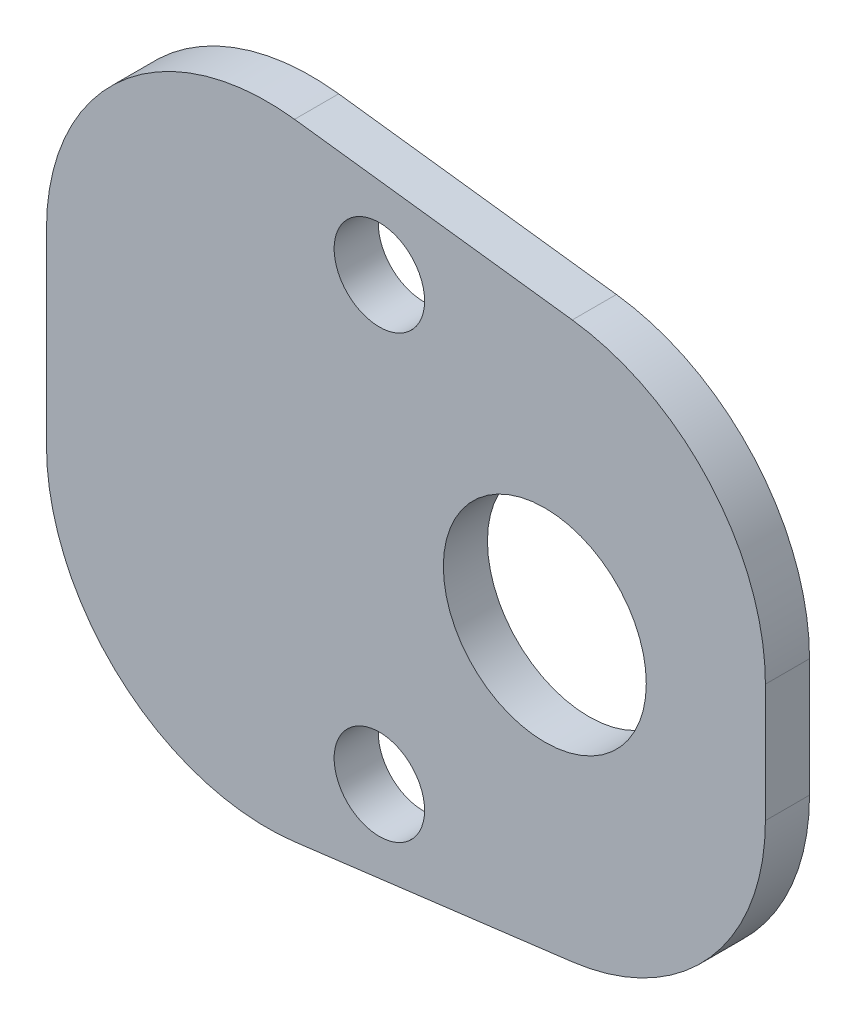
SolidWorks part; units mm, degrees
ref_plane "前视基准面" through (0, 0, 0) normal (0, 0, 1) x (1, 0, 0)
ref_plane "上视基准面" through (0, 0, 0) normal (0, 1, 0) x (1, 0, 0)
ref_plane "右视基准面" through (0, 0, 0) normal (1, 0, 0) x (0, 0, -1)
sketch "草图1" plane through (0, 0, 0) normal (0, 0, 1) x (1, 0, 0)
  line L0 (-22.499, 0) -> (-38.999, 0) construction
  line L12 (-3.7531, 12.6002) -> (-16.3433, 14.1812)
  line L36 (-9.489, 1) -> (-9.489, -1) construction
  line L40 (-0.509, 1) -> (-0.509, -1) construction
  line L41 (-3.7531, -12.6002) -> (-16.3433, -14.1812)
  line L45 (5.001, 2.6782) -> (5.001, -2.6782)
  line L47 (-27.5892, -4.2591) -> (-27.5892, 4.2591)
  circle A3 centre (-38.999, 0) radius 3 construction
  circle A6 centre (-12.499, 10) radius 2.05
  circle A37 centre (-4.999, 0) radius 4.6
  circle A43 centre (-12.499, -10) radius 2.05
  arc A47 (-3.7531, -12.6002) -> (5.001, -2.6782) centre (-4.999, -2.6782) ccw
  arc A48 (-3.7531, 12.6002) -> (5.001, 2.6782) centre (-4.999, 2.6782) cw
  arc A49 (-16.3433, 14.1812) -> (-27.5892, 4.2591) centre (-17.5892, 4.2591) ccw
  arc A50 (-27.5892, -4.2591) -> (-16.3433, -14.1812) centre (-17.5892, -4.2591) ccw
  point P7 (5.001, -11.501)
  point P11 (5.001, 11.501)
  point P14 (-27.5892, 15.5933)
  point P22 (-27.5892, -15.5933)
  dimension "D3" = 10
  dimension "D4" = 10
  dimension "D5" = 9.2
  dimension "D6" = 10
  dimension "D2" = 10
  dimension "D1" = 16.5
extrude "凸台-拉伸1" add sketch "草图1" along normal blind 2
